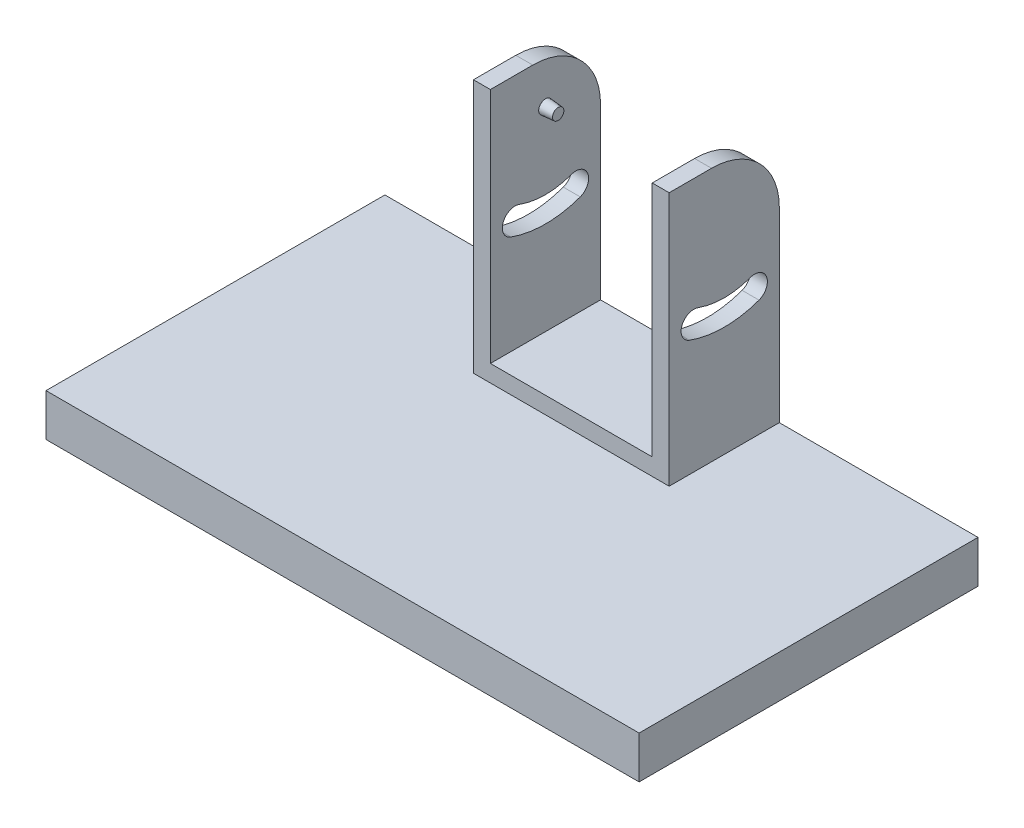
SolidWorks part; units mm, degrees
ref_plane "Спереди" through (0, 0, 0) normal (0, 0, 1) x (1, 0, 0)
ref_plane "Сверху" through (0, 0, 0) normal (0, 1, 0) x (1, 0, 0)
ref_plane "Справа" through (0, 0, 0) normal (1, 0, 0) x (0, 0, -1)
other "Configuration Table"
sketch "Sketch2" plane through (0, 0, 0) normal (0, 1, 0) x (1, 0, 0)
  line L0 (-15.5771, 0) -> (15.5771, 0) construction
  line L2 (9.55, -6.5) -> (-9.55, -6.5)
  line L3 (9.55, -6.5) -> (9.55, 6.5)
  line L4 (9.55, 6.5) -> (-9.55, 6.5)
  line L5 (-9.55, -6.5) -> (-9.55, 6.5)
  line L6 (9.55, -6.5) -> (-9.55, 6.5) construction
  line L7 (9.55, 6.5) -> (-9.55, -6.5) construction
  point P3 (0, 0)
  point P5 (0, 0)
  dimension "D1" = 19.1
  dimension "D2" = 13
extrude "Boss-Extrude1" add sketch "Sketch2" along normal blind 2
sketch "Sketch3" plane through (-9.55, 0, 0) normal (-1, 0, 0) x (0, 0, 1)
  line L0 (6.5, 0) -> (6.5, 30)
  line L1 (0, 0) -> (0, 30.8799) construction
  line L2 (6.5, 30) -> (1.5, 30)
  line L3 (-6.5, 22) -> (-6.5, 0)
  line L4 (-6.5, 0) -> (6.5, 0) construction
  line L5 (-6.5, 2) -> (-6.5, 0) construction
  line L6 (-6.5, 0) -> (6.5, 0)
  circle A0 centre (0, 25) radius 0.8 construction
  arc A1 (1.5, 30) -> (-6.5, 22) centre (1.5, 22) ccw
  dimension "D2" = 25
  dimension "D3" = 8
  dimension "D4" = 1.6
  dimension "D1" = 30
extrude "Boss-Extrude2" add sketch "Sketch3" along normal blind 2
sketch "Sketch4" plane through (-9.55, 0, 0) normal (1, 0, 0) x (0, 0, -1)
  circle A0 centre (0, 25) radius 0.8
  dimension "D1" = 1.6
extrude "Boss-Extrude3" add sketch "Sketch4" along normal blind 1.5 draft 5
mirror "Mirror1" about plane through (0, 0, 0) normal (1, 0, 0) of "Boss-Extrude3", "Boss-Extrude2"
sketch "Sketch5" plane through (-9.55, 0, 0) normal (1, 0, 0) x (0, 0, -1)
  line L0 (0, 25) -> (0, 16) construction
  line L1 (0, 0) -> (0, 30.8799) construction
  line L2 (0, 16) -> (0, 14.5) construction
  line L3 (0, 25) -> (-3.5912, 15.1332) construction
  line L4 (0, 25) -> (3.5912, 15.1332) construction
  line L5 (-3.5912, 15.1332) -> (3.5912, 15.1332) construction
  line L6 (-3.0782, 16.5428) -> (-5.3147, 10.3979) construction
  line L7 (3.0782, 16.5428) -> (5.3406, 10.3268) construction
  circle A0 centre (0, 14.5) radius 1.5 construction
  arc A1 (0, 14.5) -> (3.5912, 15.1332) centre (0, 25) ccw construction
  arc A2 (0, 14.5) -> (-3.5912, 15.1332) centre (0, 25) cw construction
  circle A3 centre (3.5912, 15.1332) radius 1.5 construction
  circle A4 centre (-3.5912, 15.1332) radius 1.5 construction
  arc A5 (-3.0782, 16.5428) -> (3.0782, 16.5428) centre (0, 25) ccw
  arc A6 (4.1042, 13.7237) -> (-4.1042, 13.7237) centre (0, 25) cw
  arc A7 (-3.0782, 16.5428) -> (-4.1042, 13.7237) centre (-3.5912, 15.1332) ccw
  arc A8 (3.0782, 16.5428) -> (4.1042, 13.7237) centre (3.5912, 15.1332) cw
  dimension "D3" = 40
  dimension "D4" = 3
  dimension "D5" = 3
  dimension "D1" = 9
  dimension "D2" = 1.5
extrude "Cut-Extrude1" cut sketch "Sketch5" against normal through all both and the other way through all contours A8 A5 A7 A6
sketch "Sketch6" plane through (0, 0, 0) normal (0, -1, 0) x (1, 0, 0)
  line L0 (11.55, -6.5) -> (-11.55, -6.5) construction
  line L1 (-35, -6.5) -> (35, -6.5)
  line L2 (-35, -6.5) -> (-35, 33.5)
  line L3 (-35, 33.5) -> (35, 33.5)
  line L4 (35, -6.5) -> (35, 33.5)
  line L5 (-35, -6.5) -> (35, 33.5) construction
  line L6 (-35, 33.5) -> (35, -6.5) construction
  point P0 (0, 13.5)
  dimension "D1" = 40
  dimension "D2" = 70
extrude "Boss-Extrude4" add sketch "Sketch6" along normal blind 5
